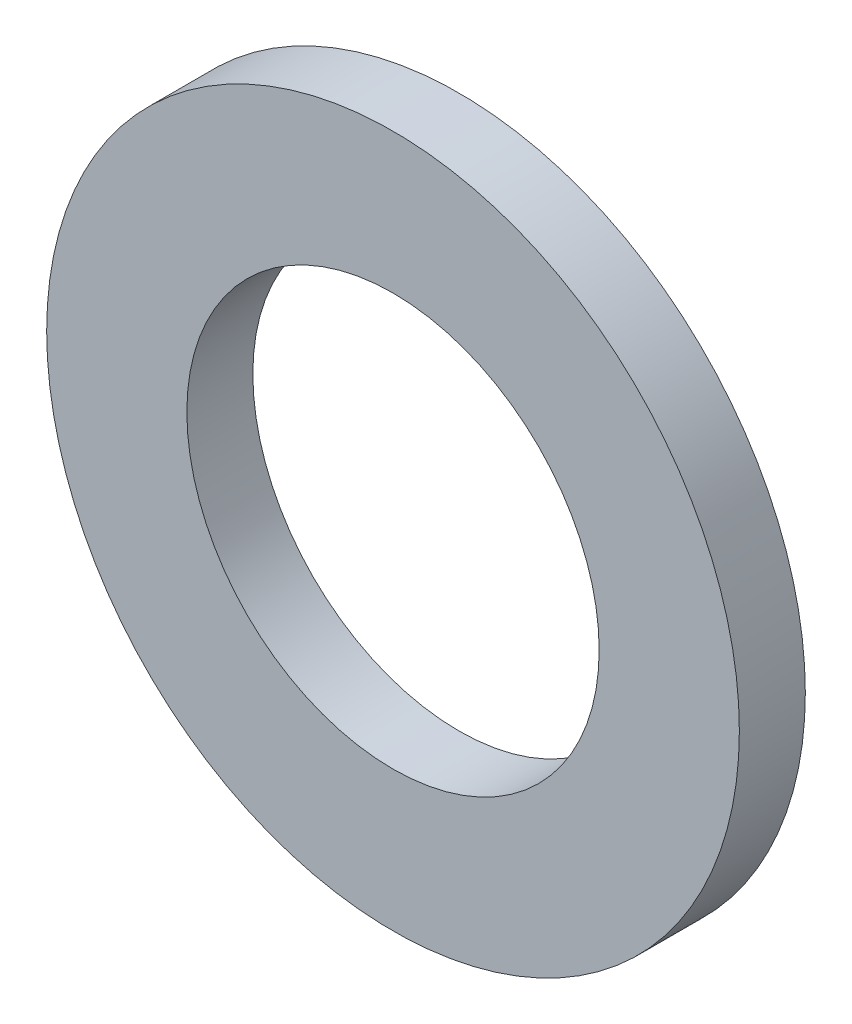
SolidWorks part; units mm, degrees
ref_plane "Front Plane" through (0, 0, 0) normal (0, 0, 1) x (1, 0, 0)
ref_plane "Top Plane" through (0, 0, 0) normal (0, 1, 0) x (1, 0, 0)
ref_plane "Right Plane" through (0, 0, 0) normal (1, 0, 0) x (0, 0, -1)
sketch "Sketch1" plane through (0, 0, 0) normal (0, 0, 1) x (1, 0, 0)
  circle A0 centre (0, 0) radius 12.5
  circle A1 centre (0, 0) radius 21
  dimension "D1" = 25
  dimension "D2" = 42
extrude "Boss-Extrude1" add sketch "Sketch1" along normal blind 4
